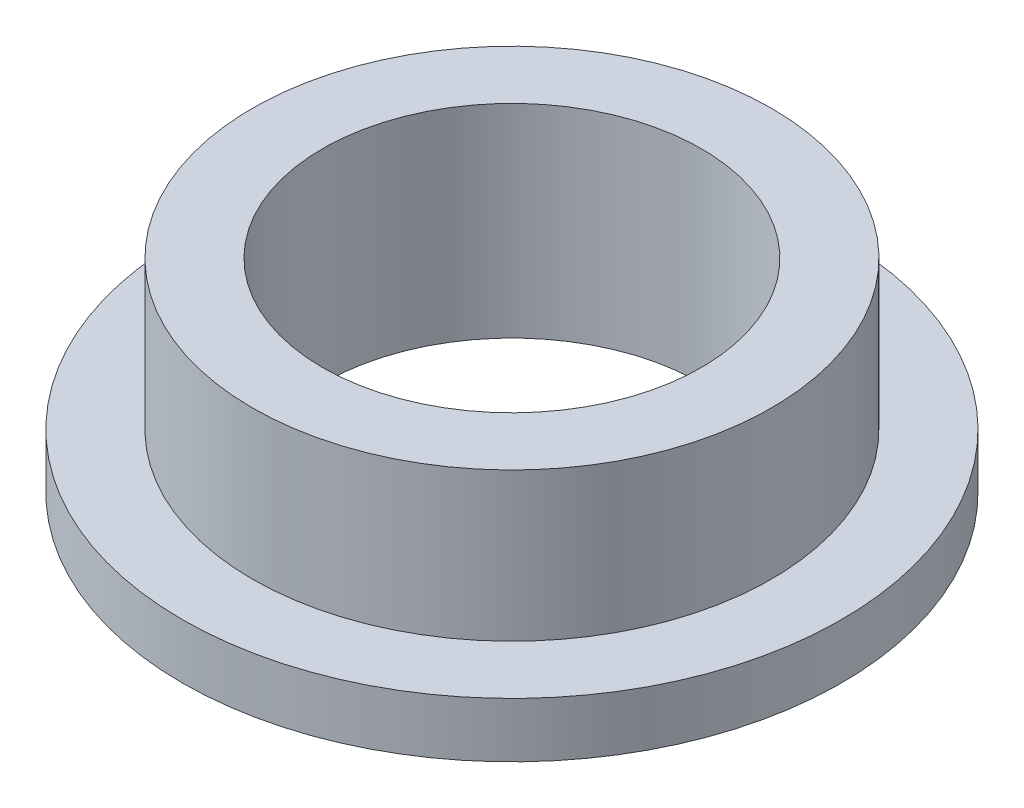
SolidWorks part; units mm, degrees
ref_plane "Front Plane" through (0, 0, 0) normal (0, 0, 1) x (1, 0, 0)
ref_plane "Top Plane" through (0, 0, 0) normal (0, 1, 0) x (1, 0, 0)
ref_plane "Right Plane" through (0, 0, 0) normal (1, 0, 0) x (0, 0, -1)
sketch "Sketch1" plane through (0, 0, 0) normal (0, 1, 0) x (1, 0, 0)
  circle A0 centre (0, 0) radius 6
  dimension "D1" = 12
extrude "Boss-Extrude1" add sketch "Sketch1" along normal blind 1
sketch "Sketch2" plane through (0, 1, 0) normal (0, 1, 0) x (1, 0, 0)
  circle A0 centre (0, 0) radius 4.725
  dimension "D1" = 9.45
extrude "Boss-Extrude2" add sketch "Sketch2" along normal blind 2.7
sketch "Sketch3" plane through (0, 3.7, 0) normal (0, 1, 0) x (1, 0, 0)
  circle A2 centre (0, 0) radius 3.45
  point P7 (2.475, 0)
  dimension "D1" = 6.9
extrude "Cut-Extrude1" cut sketch "Sketch3" against normal through all
